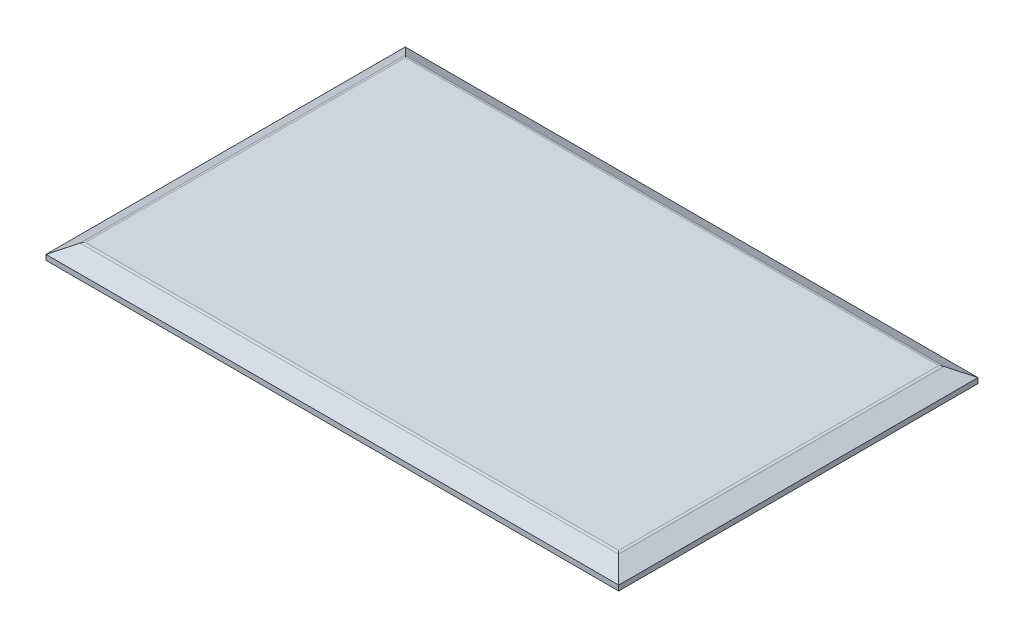
SolidWorks part; units mm, degrees
ref_plane "Front Plane" through (0, 0, 0) normal (0, 0, 1) x (1, 0, 0)
ref_plane "Top Plane" through (0, 0, 0) normal (0, 1, 0) x (1, 0, 0)
ref_plane "Right Plane" through (0, 0, 0) normal (1, 0, 0) x (0, 0, -1)
sketch "Sketch1" plane through (0, 0, 0) normal (0, 1, 0) x (1, 0, 0)
  line L1 (-55, 34.5) -> (55, 34.5)
  line L2 (-55, 34.5) -> (-55, -34.5)
  line L3 (-55, -34.5) -> (55, -34.5)
  line L4 (55, 34.5) -> (55, -34.5)
  line L5 (-55, 34.5) -> (55, -34.5) construction
  line L6 (-55, -34.5) -> (55, 34.5) construction
  point P0 (0, 0)
  dimension "D1" = 110
  dimension "D2" = 69
extrude "Boss-Extrude1" add sketch "Sketch1" along normal blind 3
chamfer "Chamfer1" distance 2 distance2 3.5 4 edges at (0, 3, 34.5) (-55, 3, 0) (0, 3, -34.5) (55, 3, 0)
fillet "Fillet1" radius 1 4 edges at (0, 3, -31) (51.5, 3, 0) (0, 3, 31) (-51.5, 3, 0)
sketch "Sketch2" plane through (0, 0, 0) normal (0, -1, 0) x (1, 0, 0)
  line L0 (55, 34.5) -> (55, -34.5) construction
  line L1 (-55, 34.5) -> (55, 34.5) construction
  line L2 (-55, 0) -> (55, 0) construction
  line L3 (-55, -34.5) -> (-55, 34.5) construction
  circle A0 centre (44, 3.5) radius 1.5
  circle A1 centre (44, -3.5) radius 1.5
  dimension "D3" = 3
  dimension "D1" = 11
  dimension "D2" = 31
extrude "Boss-Extrude2" add sketch "Sketch2" along normal blind 0.5
